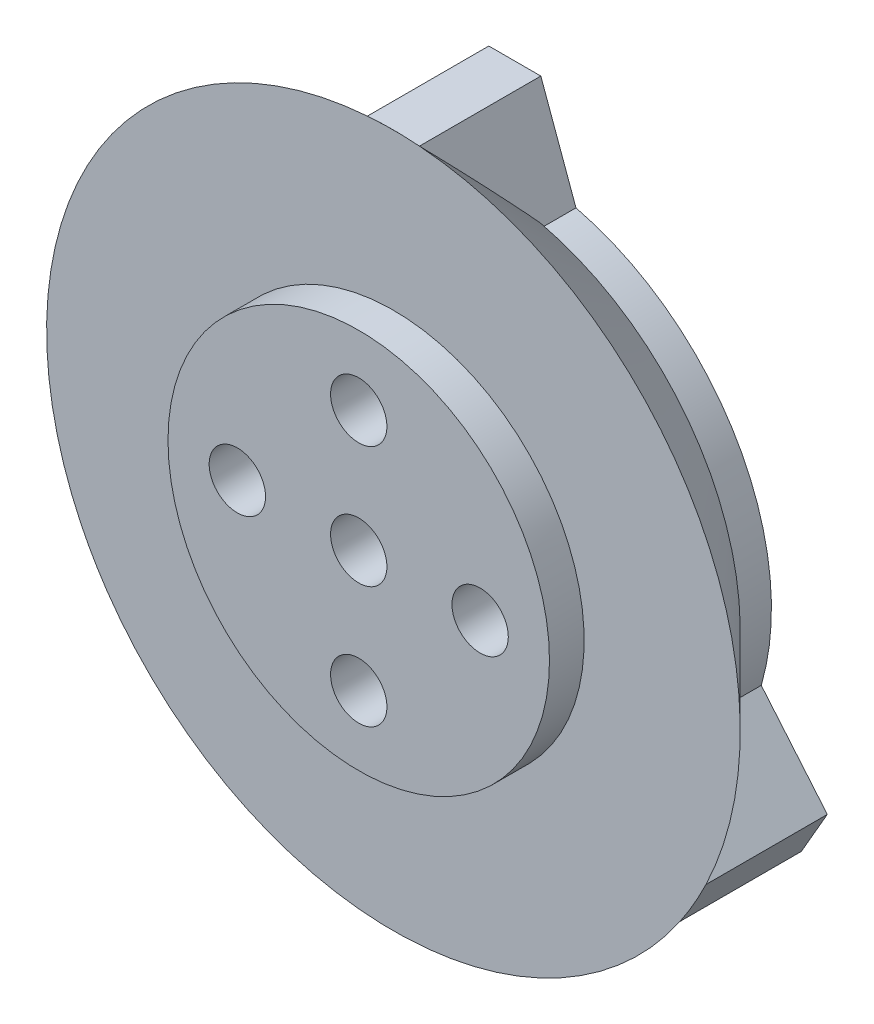
SolidWorks part; units mm, degrees
ref_plane "Plan de face" through (0, 0, 0) normal (0, 0, 1) x (1, 0, 0)
ref_plane "Plan de dessus" through (0, 0, 0) normal (0, 1, 0) x (1, 0, 0)
ref_plane "Plan de droite" through (0, 0, 0) normal (1, 0, 0) x (0, 0, -1)
sketch "Esquisse2" plane through (0, 0, 0) normal (1, 0, 0) x (0, 0, -1)
  line L0 (0, 0) -> (14.8052, 0) construction
  line L1 (0, 0) -> (0, 20)
  line L2 (0, 20) -> (5, 15)
  line L3 (5, 15) -> (5, 0)
  line L4 (5, 0) -> (0, 0)
  dimension "D1" = 40
  dimension "D2" = 15
  dimension "D3" = 5
revolve "Révolution1" add sketch "Esquisse2" angle 360 about L0
sketch "Esquisse3" plane through (0, 0, -5) normal (0, 0, -1) x (-1, 0, 0)
  circle A2 centre (0, 0) radius 14.8
  circle A3 centre (0, 0) radius 14.8
  dimension "D1" = 0.2
extrude "Boss.-Extru.1" add sketch "Esquisse3" along normal blind 2
sketch "Esquisse4" plane through (0, 0, 0) normal (0, 0, 1) x (1, 0, 0)
  line L0 (1.5, 19.9437) -> (-1.5, 19.9437)
  line L1 (-1.5, 19.9437) -> (-3.5274, 14.3735)
  line L2 (0, 0) -> (0, 7.1978) construction
  line L3 (1.5, 19.9437) -> (3.5274, 14.3735)
  circle A0 centre (0, 0) radius 14.8 construction
  circle A1 centre (0, 0) radius 20 construction
  arc A2 (3.5274, 14.3735) -> (-3.5274, 14.3735) centre (0, 0) ccw
  point P5 (0, 19.9437)
  dimension "D1" = 3
  dimension "D2" = 110
extrude "Boss.-Extru.2" add sketch "Esquisse4" against normal up to surface (7 mm away) up to face at (-14.8, 0, -7)
pattern_circular "Répétition circulaire1" count 3 over 360 about axis through (0, 0, 0) along (0, 0, 1) of "Boss.-Extru.2"
sketch "Esquisse5" plane through (0, 0, 0) normal (0, 0, 1) x (1, 0, 0)
  circle A0 centre (0, 0) radius 7 construction
  circle A1 centre (0, 7) radius 1.625
  circle A2 centre (0, 0) radius 1.625
  circle A3 centre (7, 0) radius 1.625
  circle A4 centre (0, -7) radius 1.625
  circle A5 centre (-7, 0) radius 1.625
  dimension "D1" = 14
  dimension "D2" = 3.25
  dimension "D3" = 4
extrude "Enlèv. mat.-Extru.1" cut sketch "Esquisse5" against normal through all both and the other way through all
sketch "Esquisse6" plane through (0, 0, 0) normal (0, 0, 1) x (1, 0, 0)
  circle A0 centre (0, 0) radius 11
  circle M1 centre (0, 7) radius 1.625
  circle M2 centre (-7, 0) radius 1.625
  circle M3 centre (0, -7) radius 1.625
  circle M4 centre (7, 0) radius 1.625
  circle M5 centre (0, 0) radius 1.625
  dimension "D1" = 22
extrude "Boss.-Extru.3" add sketch "Esquisse6" along normal blind 2 contours A0 M1 M3 M5 M4 M2
